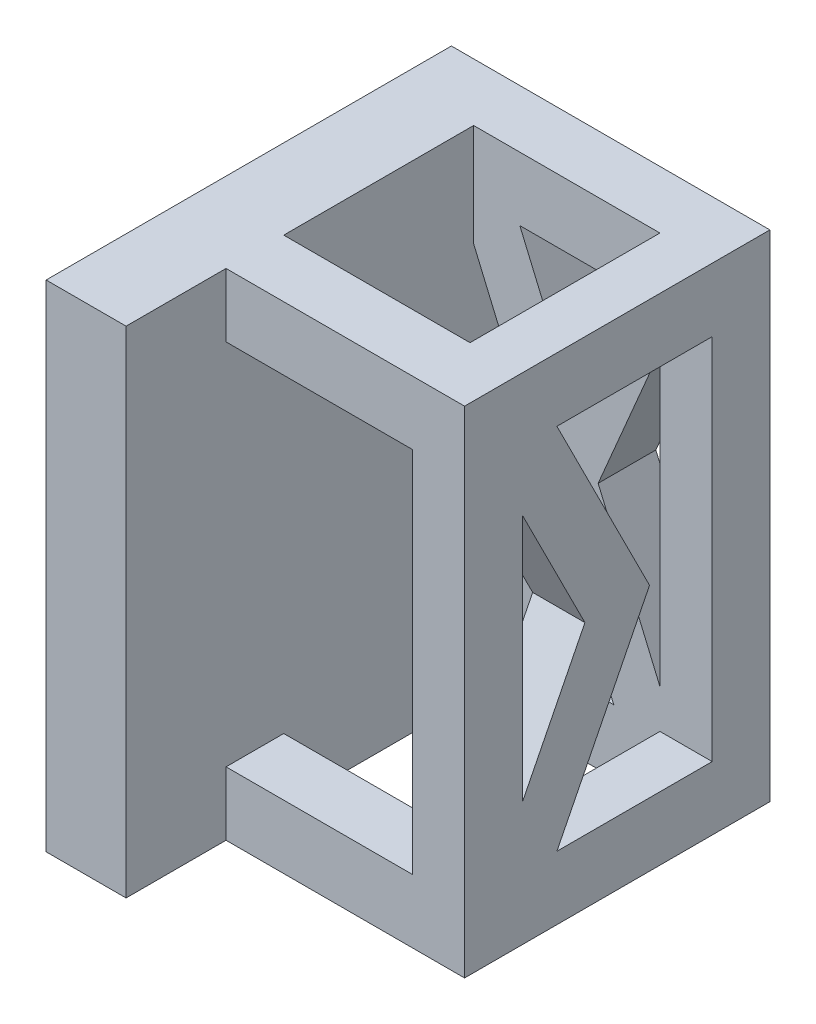
SolidWorks part; units mm, degrees
ref_plane "Front Plane" through (0, 0, 0) normal (0, 0, 1) x (1, 0, 0)
ref_plane "Top Plane" through (0, 0, 0) normal (0, 1, 0) x (1, 0, 0)
ref_plane "Right Plane" through (0, 0, 0) normal (1, 0, 0) x (0, 0, -1)
sketch "Sketch1" plane through (0, 0, -77.8375) normal (0, 0, -1) x (-1, 0, 0)
  line L1 (10.25, 37.25) -> (19.05, 37.25)
  line L2 (10.25, 37.25) -> (10.25, -17.25)
  line L3 (10.25, -17.25) -> (19.05, -17.25)
  line L4 (19.05, 37.25) -> (19.05, -17.25)
  line L5 (19.05, -76.2) -> (19.05, 76.2) construction
  line L7 (10, 28.5) -> (10, -8.5) construction
  line L9 (3.75, -17) -> (-3.75, -17) construction
  line L10 (3.75, 37) -> (-3.75, 37) construction
  dimension "D1" = 0.25
  dimension "D2" = 0.25
  dimension "D3" = 0.25
extrude "Boss-Extrude2" add sketch "Sketch1" against normal up to surface (38 mm away) and the other way offset from surface (0.25 mm away) 0.25
sketch "Sketch2" plane through (0, 0, -50.8375) normal (0, 0, -1) x (-1, 0, 0)
  line L1 (10.25, -10.25) -> (-16, -10.25)
  line L2 (10.25, -10.25) -> (10.25, -17.25)
  line L3 (10.25, -17.25) -> (-16, -17.25)
  line L4 (-16, -10.25) -> (-16, -17.25)
  line L5 (10.25, -17.25) -> (19.05, -17.25) construction
  line L6 (-8.5, -10) -> (8.5, -10) construction
  line L7 (-10, -15.5) -> (-10, -8.5) construction
  line L8 (-10, 28.5) -> (-10, -8.5) construction
  line L9 (-16, -10.25) -> (-10.25, -10.25)
  line L10 (-16, -10.25) -> (-16, 37.25)
  line L11 (-16, 37.25) -> (-10.25, 37.25)
  line L12 (-10.25, -10.25) -> (-10.25, 37.25)
  line L13 (3.75, 37) -> (-3.75, 37) construction
  line L14 (10.25, 37.25) -> (10.25, -17.25) construction
  line L15 (-10.25, 37.25) -> (10.25, 37.25)
  line L16 (-10.25, 37.25) -> (-10.25, 30.25)
  line L17 (-10.25, 30.25) -> (10.25, 30.25)
  line L18 (10.25, 37.25) -> (10.25, 30.25)
  line L19 (8.5, 30) -> (-8.5, 30) construction
  point P26 (0, 0)
  point P27 (0, 0)
  dimension "D1" = 0.25
  dimension "D2" = 6
  dimension "D3" = 0.25
  dimension "D4" = 0.25
  dimension "D5" = 0.25
extrude "Boss-Extrude3" add sketch "Sketch2" along normal blind 6.35 contours L1 L12 L11 L10 | L15 L18 L17 L16
sketch "Sketch3" plane through (0, 0, -78.0875) normal (0, 0, -1) x (-1, 0, 0)
  line L0 (19.05, -17.25) -> (19.05, 37.25) construction
  line L1 (19.05, 37.25) -> (10.25, 37.25)
  line L2 (19.05, 37.25) -> (19.05, -17.25)
  line L3 (19.05, -17.25) -> (10.25, -17.25)
  line L4 (10.25, 37.25) -> (10.25, -17.25)
  line L5 (19.05, -76.2) -> (19.05, 76.2) construction
  line L6 (10.25, -17.25) -> (19.05, -17.25) construction
  line L7 (10.25, -10.25) -> (10.25, -17.25) construction
  line L8 (19.05, 37.25) -> (10.25, 37.25) construction
  line L9 (10.25, -17.25) -> (-16, -17.25) construction
  line L10 (-16, 37.25) -> (-10.25, 37.25)
  line L11 (-16, 37.25) -> (-16, -17.25)
  line L12 (-16, -17.25) -> (-10.25, -17.25)
  line L13 (-10.25, 37.25) -> (-10.25, -17.25)
  line L14 (-10.25, -10.25) -> (-10.25, 30.25) construction
  line L15 (-5.17, -10.25) -> (10.25, 25.9714)
  line L16 (-10.25, 37.25) -> (10.25, 37.25)
  line L17 (-10.25, 37.25) -> (-10.25, 30.25)
  line L18 (-10.25, 30.25) -> (10.25, 30.25)
  line L19 (10.25, 37.25) -> (10.25, 30.25)
  line L20 (10.25, -17.25) -> (-10.25, -17.25)
  line L21 (10.25, -17.25) -> (10.25, -10.25)
  line L22 (10.25, -10.25) -> (-10.25, -10.25)
  line L23 (-10.25, -17.25) -> (-10.25, -10.25)
  line L24 (5.17, 30.25) -> (-10.25, -5.9714)
  line L25 (-10.25, 25.9714) -> (5.17, -10.25)
  line L26 (-5.17, 30.25) -> (10.25, -5.9714)
  line M6 (19.05, 37.25) -> (10.25, 37.25)
  line M7 (10.25, 37.25) -> (10.25, -17.25)
  line M8 (10.25, -17.25) -> (19.05, -17.25)
  line M9 (19.05, -17.25) -> (19.05, 37.25)
  dimension "D1" = 6.35
  dimension "D2" = 6.35
  dimension "D3" = 5.08
  dimension "D4" = 5.08
  dimension "D5" = 5.08
  dimension "D6" = 5.08
extrude "Boss-Extrude4" add sketch "Sketch3" along normal blind 6.35 contours L13 L18 L16 M7 | L13 L10 L11 L12 | L4 M9 M6 M7 M8 | L24 L26 L15 L4 L18 | L26 L18 L13 L25 L24 | L26 L24 L25 L15 | L25 L24 L13 L22 L15 | L26 L15 L25 L22 M7 | L22 L13 L20 M7
sketch "Sketch4" plane through (16, 0, 0) normal (1, 0, 0) x (0, 0, -1)
  line L0 (78.0875, 37.25) -> (78.0875, -17.25) construction
  line L1 (57.1875, 37.25) -> (78.0875, 37.25)
  line L2 (57.1875, 37.25) -> (57.1875, 30.25)
  line L3 (57.1875, 30.25) -> (78.0875, 30.25)
  line L4 (78.0875, 37.25) -> (78.0875, 30.25)
  line L5 (57.1875, -10.25) -> (57.1875, -17.25) construction
  line L6 (78.0875, -17.25) -> (57.1875, -17.25)
  line L7 (78.0875, -17.25) -> (78.0875, -10.25)
  line L8 (78.0875, -10.25) -> (57.1875, -10.25)
  line L9 (57.1875, -17.25) -> (57.1875, -10.25)
  line L10 (77.8375, 30) -> (50.8375, 30) construction
  line L11 (77.8375, -10) -> (50.8375, -10) construction
  line L12 (57.1875, 23.6965) -> (74.2775, -10.25)
  line L13 (57.1875, -17.25) -> (57.1875, 37.25) construction
  line L14 (60.9975, 30.25) -> (78.0875, -3.6965)
  line L15 (74.2775, 30.25) -> (57.1875, -3.6965)
  line L16 (60.9975, -10.25) -> (78.0875, 23.6965)
  line L17 (78.0875, -5.9714) -> (78.0875, -17.25) construction
  point P28 (59.3009, -10.25)
  point P29 (76.0456, -10.25)
  point P32 (0, 0)
  line M11 (57.1875, -17.25) -> (57.1875, 37.25)
  dimension "D1" = 0.25
  dimension "D2" = 0.25
  dimension "D3" = 6.35
  dimension "D4" = 6.35
  dimension "D5" = 3.81
  dimension "D6" = 3.81
  dimension "D7" = 3.81
  dimension "D8" = 3.81
extrude "Boss-Extrude5" add sketch "Sketch4" against normal up to surface (5.75 mm away) contours L8 L16 L12 L15 M11 | L7 L8 L6 M11 | L12 L16 L14 L15 | L4 L1 L3 M11 | L15 L14 L3 L12 M11 up to face at (10.25, 10, -54.0125)
equation "\"D2@Sketch3\"=\"D1@Sketch3\""
equation "\"D4@Sketch3\"=\"D3@Sketch3\""
equation "\"D5@Sketch3\"=\"D3@Sketch3\""
equation "\"D6@Sketch3\"=\"D3@Sketch3\""
equation "\"D4@Sketch4\"=\"D3@Sketch4\""
equation "\"D6@Sketch4\"=\"D5@Sketch4\""
equation "\"D7@Sketch4\"=\"D5@Sketch4\""
equation "\"D8@Sketch4\"=\"D5@Sketch4\""
